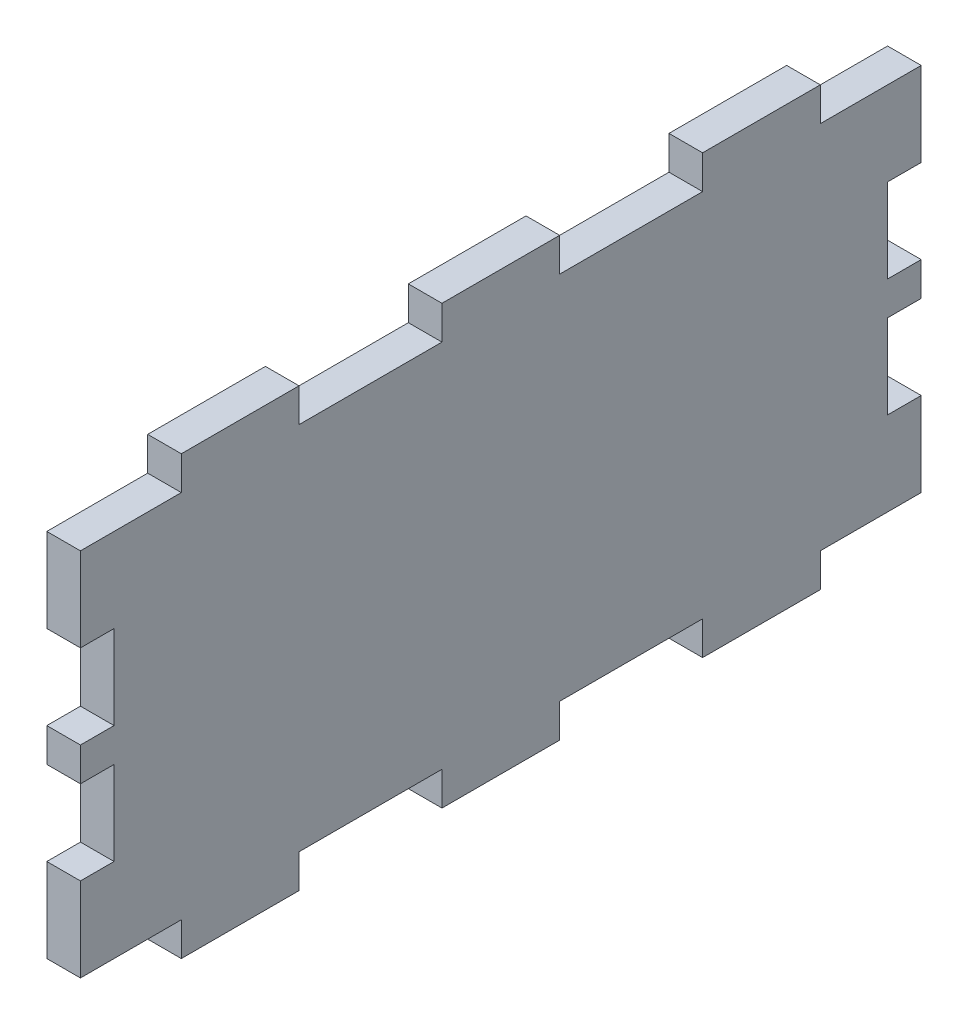
SolidWorks part; units mm, degrees
ref_plane "Front Plane" through (0, 0, 0) normal (0, 0, 1) x (1, 0, 0)
ref_plane "Top Plane" through (0, 0, 0) normal (0, 1, 0) x (1, 0, 0)
ref_plane "Right Plane" through (0, 0, 0) normal (1, 0, 0) x (0, 0, -1)
sketch "Sketch1" plane through (0, 0, 0) normal (1, 0, 0) x (0, 0, -1)
  line L1 (-25, 11) -> (25, 11)
  line L2 (-25, 11) -> (-25, -11)
  line L3 (-25, -11) -> (25, -11)
  line L4 (25, 11) -> (25, -11)
  line L5 (-25, 11) -> (25, -11) construction
  line L6 (-25, -11) -> (25, 11) construction
  line L7 (-19, -11) -> (-12, -11)
  line L8 (-19, -11) -> (-19, -13)
  line L9 (-19, -13) -> (-12, -13)
  line L10 (-12, -11) -> (-12, -13)
  line L11 (-3.5, -11) -> (3.5, -11)
  line L12 (-3.5, -11) -> (-3.5, -13)
  line L13 (-3.5, -13) -> (3.5, -13)
  line L14 (3.5, -11) -> (3.5, -13)
  line L15 (12, -11) -> (19, -11)
  line L16 (12, -11) -> (12, -13)
  line L17 (12, -13) -> (19, -13)
  line L18 (19, -11) -> (19, -13)
  line L19 (-19, 11) -> (-12, 11)
  line L20 (-19, 11) -> (-19, 13)
  line L21 (-19, 13) -> (-12, 13)
  line L22 (-12, 11) -> (-12, 13)
  line L23 (-3.5, 11) -> (3.5, 11)
  line L24 (-3.5, 11) -> (-3.5, 13)
  line L25 (-3.5, 13) -> (3.5, 13)
  line L26 (3.5, 11) -> (3.5, 13)
  line L27 (12, 11) -> (19, 11)
  line L28 (12, 11) -> (12, 13)
  line L29 (12, 13) -> (19, 13)
  line L30 (19, 11) -> (19, 13)
  line L31 (-25, -1) -> (-23, -1)
  line L32 (-25, -1) -> (-25, -6)
  line L33 (-25, -6) -> (-23, -6)
  line L34 (-23, -1) -> (-23, -6)
  line L35 (23, -1) -> (25, -1)
  line L36 (23, -1) -> (23, -6)
  line L37 (23, -6) -> (25, -6)
  line L38 (25, -1) -> (25, -6)
  line L39 (-25, 6) -> (-23, 6)
  line L40 (-25, 6) -> (-25, 1)
  line L41 (-25, 1) -> (-23, 1)
  line L42 (-23, 6) -> (-23, 1)
  line L43 (23, 6) -> (25, 6)
  line L44 (23, 6) -> (23, 1)
  line L45 (23, 1) -> (25, 1)
  line L46 (25, 6) -> (25, 1)
  point P0 (0, 0)
  dimension "D1" = 50
  dimension "D2" = 7
  dimension "D3" = 7
  dimension "D4" = 7
  dimension "D5" = 7
  dimension "D6" = 7
  dimension "D7" = 7
  dimension "D8" = 6
  dimension "D9" = 8.5
  dimension "D10" = 8.5
  dimension "D11" = 6
  dimension "D12" = 6
  dimension "D13" = 8.5
  dimension "D14" = 8.5
  dimension "D15" = 6
  dimension "D16" = 22
  dimension "D17" = 2
  dimension "D18" = 2
  dimension "D19" = 2
  dimension "D20" = 2
  dimension "D21" = 2
  dimension "D22" = 2
  dimension "D23" = 5
  dimension "D24" = 5
  dimension "D25" = 5
  dimension "D26" = 5
  dimension "D27" = 5
  dimension "D28" = 5
  dimension "D29" = 5
  dimension "D30" = 5
  dimension "D31" = 0
  dimension "D32" = 0
  dimension "D33" = 46
  dimension "D34" = 0
  dimension "D35" = 0
  dimension "D37" = 0
  dimension "D38" = 0
extrude "Boss-Extrude1" add sketch "Sketch1" along normal blind 2 contours L4 L1 L2 L3 | L1 L26 L25 L24 | L1 L30 L29 L28 | L18 L3 L16 L17 | L14 L3 L12 L13 | L10 L3 L8 L9 | L22 L21 L20 L19
